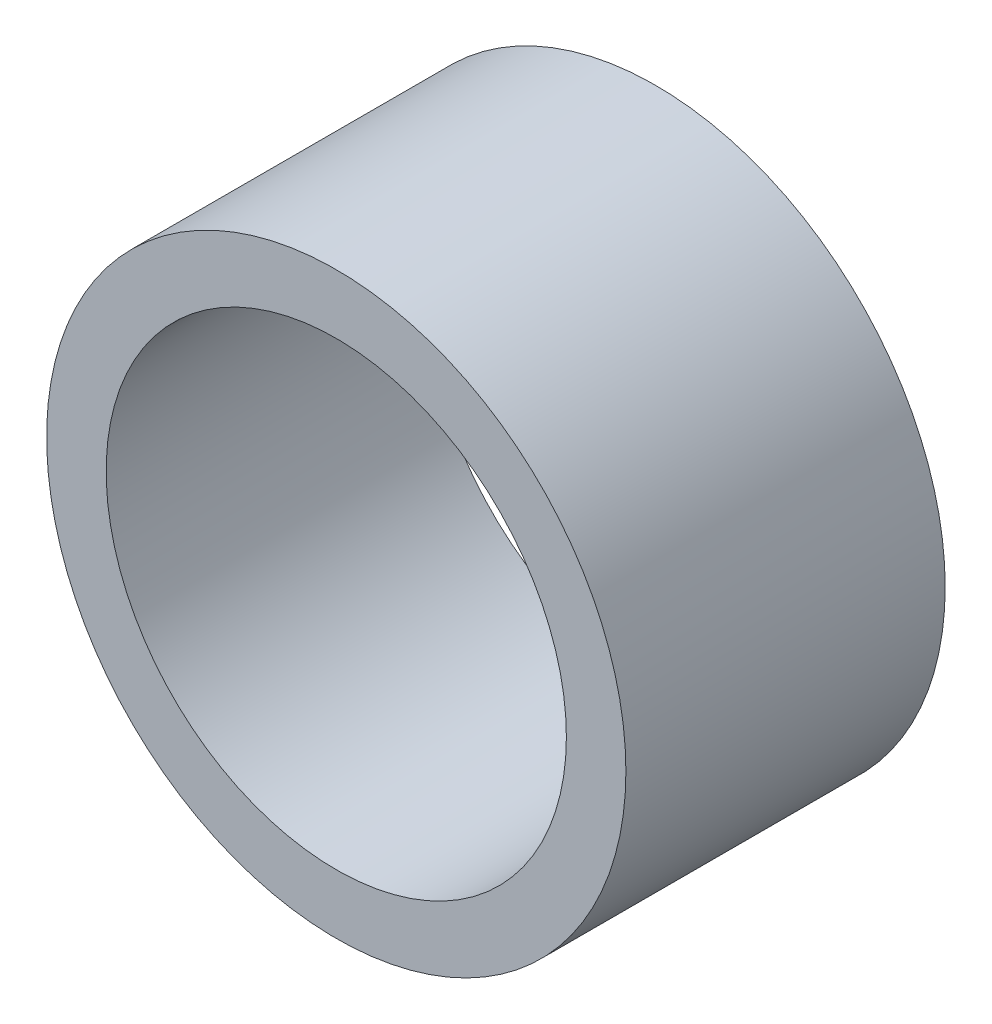
SolidWorks part; units mm, degrees
material "Alloy Steel"
ref_plane "Front" through (0, 0, 0) normal (0, 0, 1) x (1, 0, 0)
ref_plane "Top" through (0, 0, 0) normal (0, 1, 0) x (1, 0, 0)
ref_plane "Right" through (0, 0, 0) normal (1, 0, 0) x (0, 0, -1)
sketch "Sketch1" plane through (0, 0, 0) normal (0, 0, 1) x (1, 0, 0)
  circle A0 centre (0, 0) radius 6.35
  circle A1 centre (0, 0) radius 5.045
  dimension "D1" = 10.09
  dimension "D2" = 12.7
extrude "Extrude1" add sketch "Sketch1" against normal blind 7
